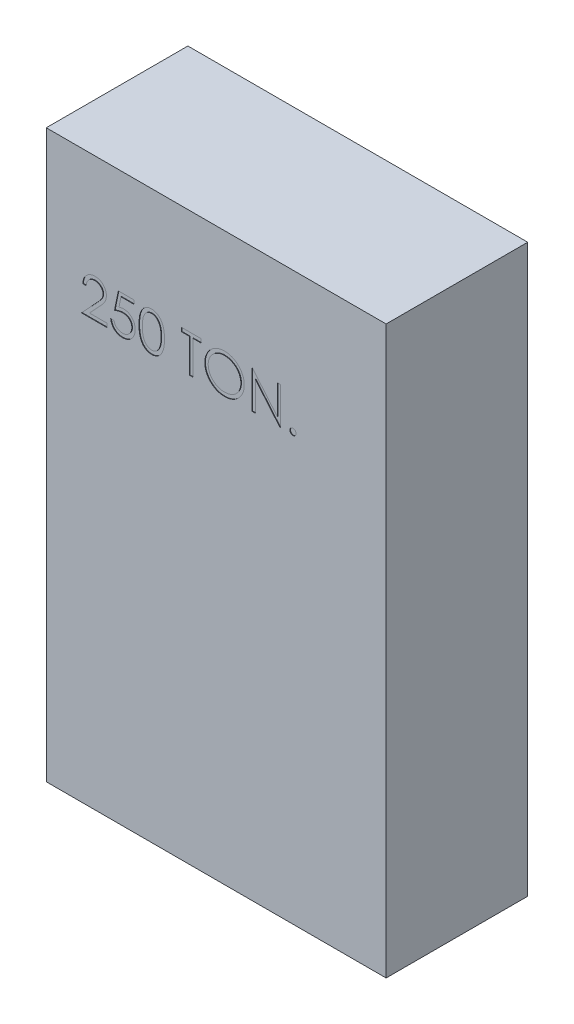
SolidWorks part; units mm, degrees
ref_plane "Alzado" through (0, 0, 0) normal (0, 0, 1) x (1, 0, 0)
ref_plane "Planta" through (0, 0, 0) normal (0, 1, 0) x (1, 0, 0)
ref_plane "Vista lateral" through (0, 0, 0) normal (1, 0, 0) x (0, 0, -1)
sketch "Croquis1" plane through (0, 0, 0) normal (0, 1, 0) x (1, 0, 0)
  line L1 (-600, 250) -> (600, 250)
  line L2 (-600, 250) -> (-600, -250)
  line L3 (-600, -250) -> (600, -250)
  line L4 (600, 250) -> (600, -250)
  line L5 (-600, 250) -> (600, -250) construction
  line L6 (-600, -250) -> (600, 250) construction
  point P0 (0, 0)
  dimension "D1" = 1200
  dimension "D2" = 500
extrude "Saliente-Extruir1" add sketch "Croquis1" along normal blind 2000
sketch "Croquis2" plane through (0, 0, 250) normal (0, 0, 1) x (1, 0, 0)
  line L0 (-481.0603, 1496.1178) -> (404.9631, 1496.1178) construction
  text T0 "250 TON." font "Century Gothic" height in points 500
  point P2 (404.9631, 1496.1178)
extrude "Cortar-Extruir1" cut sketch "Croquis2" against normal blind 2
